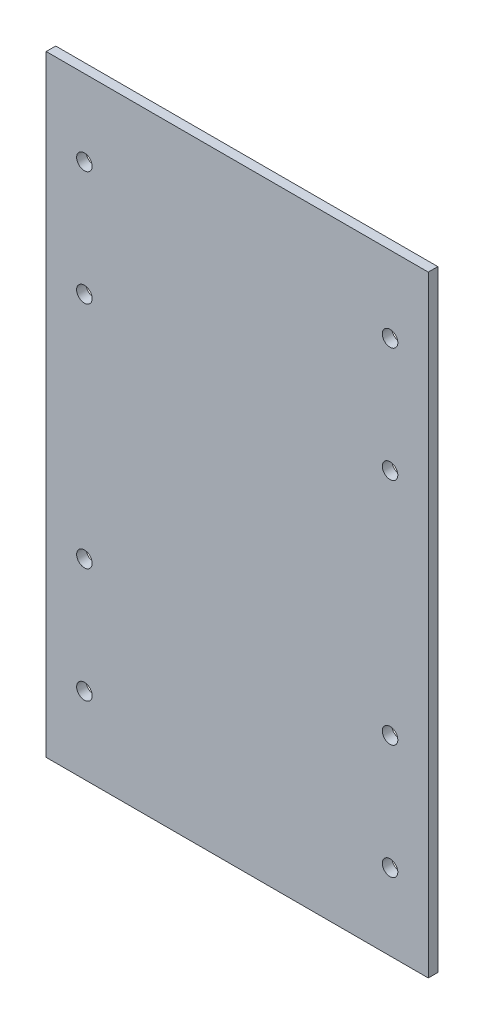
SolidWorks part; units mm, degrees
ref_plane "Front Plane" through (0, 0, 0) normal (0, 0, 1) x (1, 0, 0)
ref_plane "Top Plane" through (0, 0, 0) normal (0, 1, 0) x (1, 0, 0)
ref_plane "Right Plane" through (0, 0, 0) normal (1, 0, 0) x (0, 0, -1)
sketch "Sketch1" plane through (0, 0, 0) normal (0, 0, 1) x (1, 0, 0)
  line L1 (-63.5, -101.6) -> (63.5, -101.6)
  line L2 (-63.5, -101.6) -> (-63.5, 101.6)
  line L3 (-63.5, 101.6) -> (63.5, 101.6)
  line L4 (63.5, -101.6) -> (63.5, 101.6)
  line L5 (-63.5, -101.6) -> (63.5, 101.6) construction
  line L6 (-63.5, 101.6) -> (63.5, -101.6) construction
  point P0 (0, 0)
  dimension "D1" = 127
  dimension "D2" = 203.2
extrude "Boss-Extrude1" add sketch "Sketch1" along normal blind 3.175
sketch "Sketch2" plane through (0, 0, 3.175) normal (0, 0, 1) x (1, 0, 0)
  line L0 (-50.8, 101.6) -> (-50.8, -101.6) construction
  line L1 (63.5, 101.6) -> (-63.5, 101.6) construction
  line L2 (-63.5, -101.6) -> (63.5, -101.6) construction
  line L3 (-63.5, 101.6) -> (-63.5, -101.6) construction
  circle A0 centre (-50.8, 76.2) radius 2.5797
  circle A1 centre (-50.8, 38.1) radius 2.5797
  circle A2 centre (-50.8, -38.1) radius 2.5797
  circle A3 centre (-50.8, -76.2) radius 2.5797
  dimension "D1" = 5.1594
  dimension "D2" = 5.1594
  dimension "D3" = 5.1594
  dimension "D4" = 5.1594
  dimension "D5" = 38.1
  dimension "D6" = 38.1
  dimension "D7" = 25.4
  dimension "D8" = 25.4
  dimension "D9" = 12.7
extrude "Cut-Extrude1" cut sketch "Sketch2" against normal blind 6.35
ref_plane "Plane1" through (0, 0, 0) normal (1, 0, 0) x (0, 0, -1)
mirror "Mirror1" about plane through (0, 0, 0) normal (1, 0, 0) of "Cut-Extrude1"
